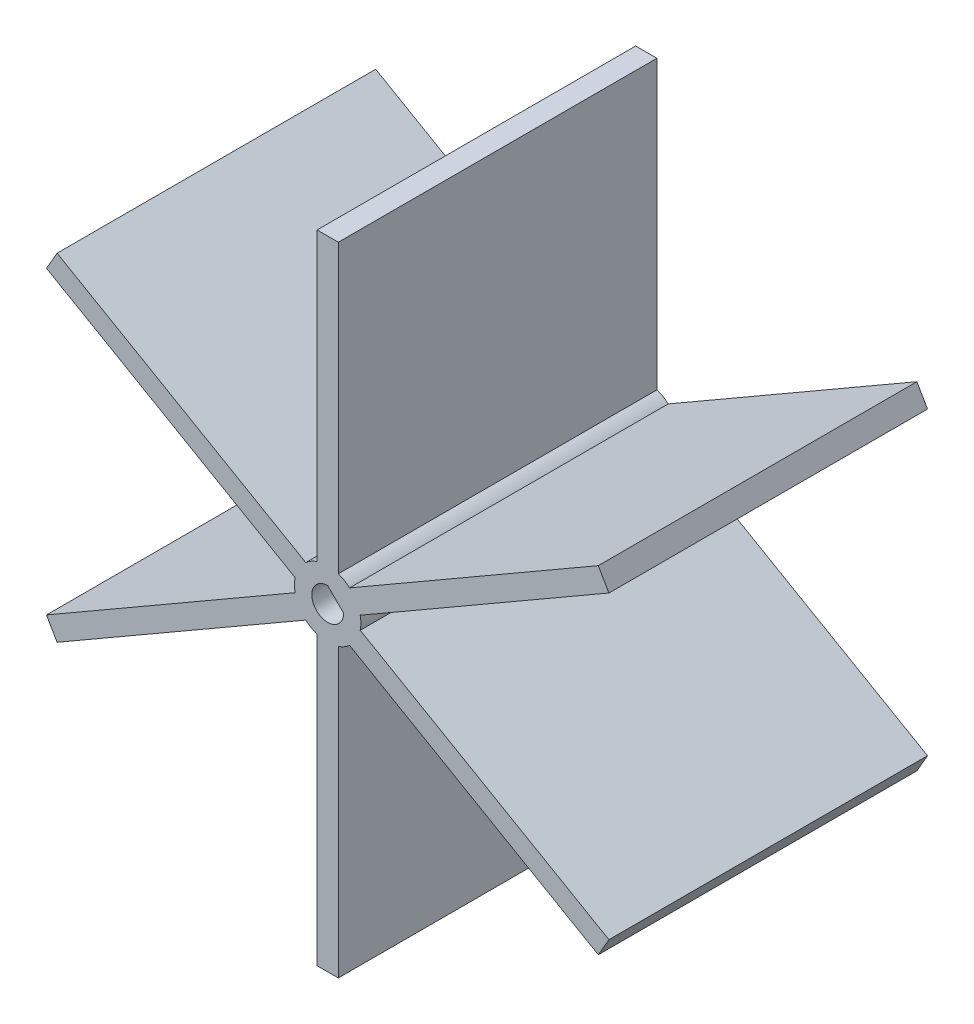
SolidWorks part; units mm, degrees
material "ABS"
ref_plane "Front Plane" through (0, 0, 0) normal (0, 0, 1) x (1, 0, 0)
ref_plane "Top Plane" through (0, 0, 0) normal (0, 1, 0) x (1, 0, 0)
ref_plane "Right Plane" through (0, 0, 0) normal (1, 0, 0) x (0, 0, -1)
sketch "Sketch1" plane through (0, 0, 0) normal (0, 0, 1) x (1, 0, 0)
  line L0 (0, 0) -> (0, 76.2)
  line L1 (0, 0) -> (65.9911, 38.1)
  line L2 (0, 0) -> (65.9911, -38.1)
  line L3 (0, 0) -> (0, -76.2)
  line L4 (0, 0) -> (-65.9911, -38.1)
  line L5 (0, 0) -> (-65.9911, 38.1)
  line L6 (2.54, 0) -> (2.54, 76.2)
  line L7 (1.27, -2.1997) -> (67.2611, 35.9003)
  line L8 (-1.27, -2.1997) -> (64.7211, -40.2997)
  line L9 (-2.54, 0) -> (-2.54, 76.2)
  line L10 (-1.27, 2.1997) -> (64.7211, 40.2997)
  line L11 (1.27, 2.1997) -> (67.2611, -35.9003)
  line L12 (-2.54, 0) -> (-2.54, -76.2)
  line L13 (-1.27, 2.1997) -> (-67.2611, -35.9003)
  line L14 (1.27, 2.1997) -> (-64.7211, 40.2997)
  line L15 (2.54, 0) -> (2.54, -76.2)
  line L16 (1.27, -2.1997) -> (-64.7211, -40.2997)
  line L17 (-1.27, -2.1997) -> (-67.2611, 35.9003)
  line L18 (-67.2611, 35.9003) -> (-64.7211, 40.2997)
  line L19 (-2.54, 76.2) -> (2.54, 76.2)
  line L20 (64.7211, 40.2997) -> (67.2611, 35.9003)
  line L21 (64.7211, -40.2997) -> (67.2611, -35.9003)
  line L22 (2.54, -76.2) -> (-2.54, -76.2)
  line L23 (-64.7211, -40.2997) -> (-67.2611, -35.9003)
  circle A0 centre (0, 0) radius 7.9375
  point P10 (0, 0)
  dimension "D7" = 15.875
  dimension "D1" = 76.2
  dimension "D3" = 2.54
  dimension "D4" = 2.54
  dimension "D5" = 2.54
  dimension "D6" = 2.54
  dimension "D2" = 6
extrude "Boss-Extrude1" add sketch "Sketch1" along normal blind 76.2 contours A0 L5 L18 L17 | A0 L14 L18 L5 | A0 L0 L19 L9 | A0 L6 L19 L0 | A0 L1 L20 L10 | A0 L7 L20 L1 | A0 L2 L21 L11 | A0 L8 L21 L2 | A0 L3 L22 L15 | A0 L12 L22 L3 | A0 L4 L23 L16 | A0 L13 L23 L4
sketch "Sketch2" plane through (0, 0, 76.2) normal (0, 0, 1) x (1, 0, 0)
  line L0 (0, 3.81) -> (3.81, 0)
  circle A0 centre (0, 0) radius 3.81
  dimension "D1" = 7.62
extrude "Cut-Extrude1" cut sketch "Sketch2" against normal through all both and the other way through all contours L0 A0
